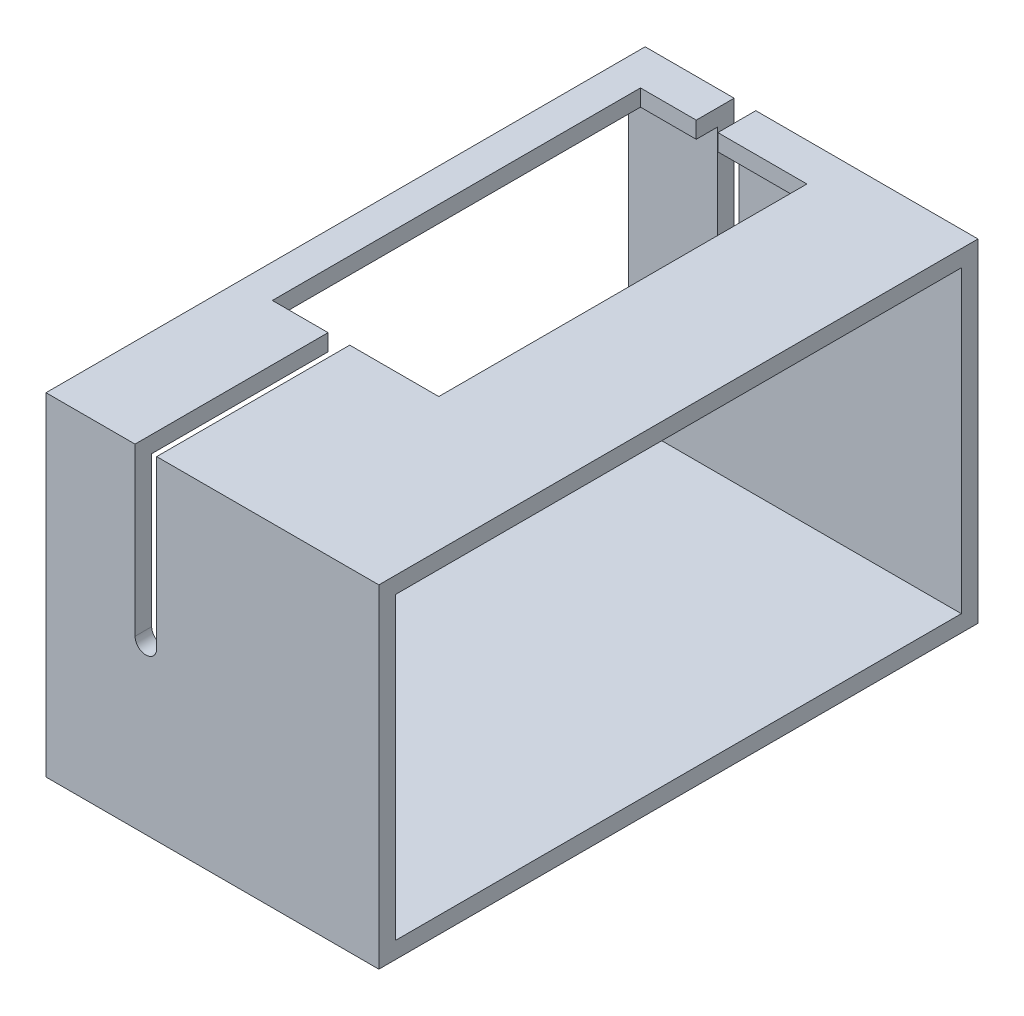
SolidWorks part; units mm, degrees
ref_plane "前视基准面" through (0, 0, 0) normal (0, 0, 1) x (1, 0, 0)
ref_plane "上视基准面" through (0, 0, 0) normal (0, 1, 0) x (1, 0, 0)
ref_plane "右视基准面" through (0, 0, 0) normal (1, 0, 0) x (0, 0, -1)
sketch "草图1" plane through (0, 0, 0) normal (0, 1, 0) x (1, 0, 0)
  line L1 (-25, 45) -> (25, 45)
  line L2 (-25, 45) -> (-25, -45)
  line L3 (-25, -45) -> (25, -45)
  line L4 (25, 45) -> (25, -45)
  line L5 (-25, 45) -> (25, -45) construction
  line L6 (-25, -45) -> (25, 45) construction
  point P0 (0, 0)
  dimension "D1" = 90
  dimension "D2" = 50
extrude "凸台-拉伸1" add sketch "草图1" along normal blind 50
sketch "草图2" plane through (0, 50, 0) normal (0, 1, 0) x (1, 0, 0)
  line L0 (25, 45) -> (-25, 45) construction
  line L1 (-20, 39.3) -> (5, 39.3)
  line L2 (-20, 39.3) -> (-20, -16)
  line L3 (-20, -16) -> (5, -16)
  line L4 (5, 39.3) -> (5, -16)
  line L5 (-25, 45) -> (-25, -45) construction
  dimension "D1" = 25
  dimension "D2" = 55.3
  dimension "D3" = 5.7
  dimension "D4" = 5
extrude "切除-拉伸1" cut sketch "草图2" against normal blind 10
sketch "草图3" plane through (-25, 0, 0) normal (-1, 0, 0) x (0, 0, 1)
  line L0 (-45, 50) -> (45, 50) construction
  line L1 (-42.5, 47.5) -> (42.5, 47.5)
  line L2 (-42.5, 47.5) -> (-42.5, 2.5)
  line L3 (-42.5, 2.5) -> (42.5, 2.5)
  line L4 (42.5, 47.5) -> (42.5, 2.5)
  line L5 (-45, 50) -> (-45, 0) construction
  line L6 (-45, 0) -> (45, 0) construction
  line L7 (45, 50) -> (45, 0) construction
  dimension "D1" = 2.5
  dimension "D2" = 2.5
  dimension "D3" = 2.5
  dimension "D4" = 2.5
extrude "切除-拉伸2" cut sketch "草图3" against normal through all
sketch "草图4" plane through (0, 0, 45) normal (0, 0, 1) x (1, 0, 0)
  line L0 (-25, 50) -> (-25, 0) construction
  line L1 (-25, 50) -> (25, 50) construction
  line L2 (-11.625, 25) -> (-11.625, 50)
  line L3 (-8.375, 25) -> (-8.375, 50)
  line L4 (-8.375, 50) -> (-11.625, 50)
  arc A0 (-11.625, 25) -> (-8.375, 25) centre (-10, 25) ccw
  dimension "D1" = 3.25
  dimension "D2" = 15
  dimension "D3" = 25
extrude "切除-拉伸3" cut sketch "草图4" against normal through all both and the other way through all
